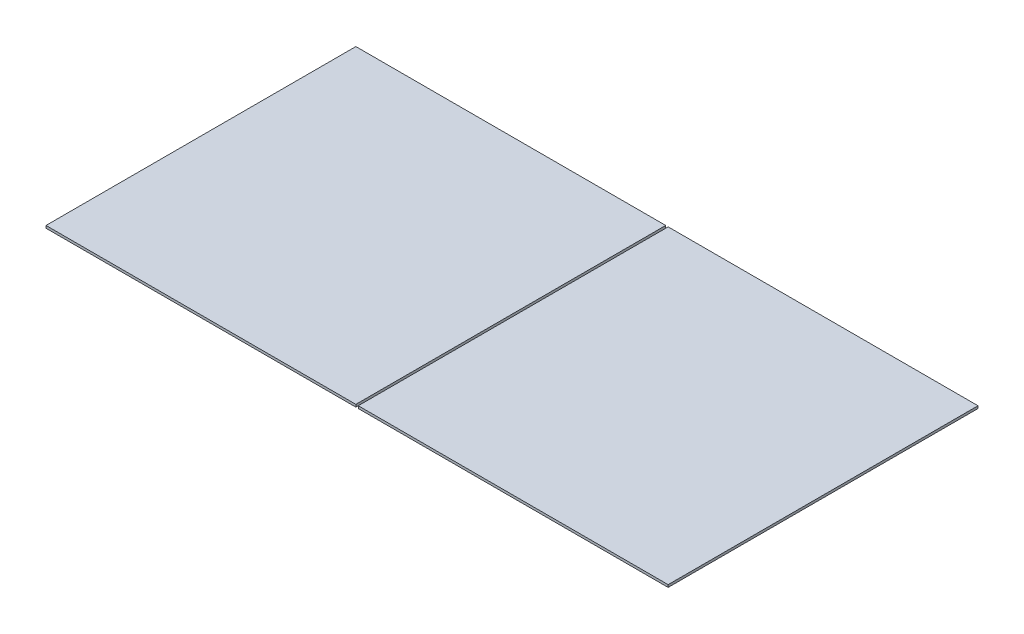
SolidWorks part; units mm, degrees
ref_plane "Front Plane" through (0, 0, 0) normal (0, 0, 1) x (1, 0, 0)
ref_plane "Top Plane" through (0, 0, 0) normal (0, 1, 0) x (1, 0, 0)
ref_plane "Right Plane" through (0, 0, 0) normal (1, 0, 0) x (0, 0, -1)
sketch "Sketch1" plane through (0, 0, 0) normal (0, 1, 0) x (1, 0, 0)
  line L0 (191.5, 63.5) -> (191.5, -63.5)
  line L1 (-63.5, 63.5) -> (63.5, 63.5)
  line L2 (-63.5, 63.5) -> (-63.5, -63.5)
  line L3 (-63.5, -63.5) -> (63.5, -63.5)
  line L4 (63.5, 63.5) -> (63.5, -63.5)
  line L5 (-63.5, 63.5) -> (63.5, -63.5) construction
  line L6 (-63.5, -63.5) -> (63.5, 63.5) construction
  line L7 (191.5, -63.5) -> (64.5, -63.5)
  line L8 (191.5, 63.5) -> (64.5, 63.5)
  line L9 (64.5, 63.5) -> (64.5, -63.5)
  line L10 (63.5, -63.5) -> (64.5, -63.5) construction
  line L11 (63.5, 63.5) -> (64.5, 63.5) construction
  point P0 (0, 0)
  dimension "D1" = 127
  dimension "D2" = 127
  dimension "D3" = 1
  dimension "D4" = 127
extrude "Boss-Extrude1" add sketch "Sketch1" along normal blind 1
